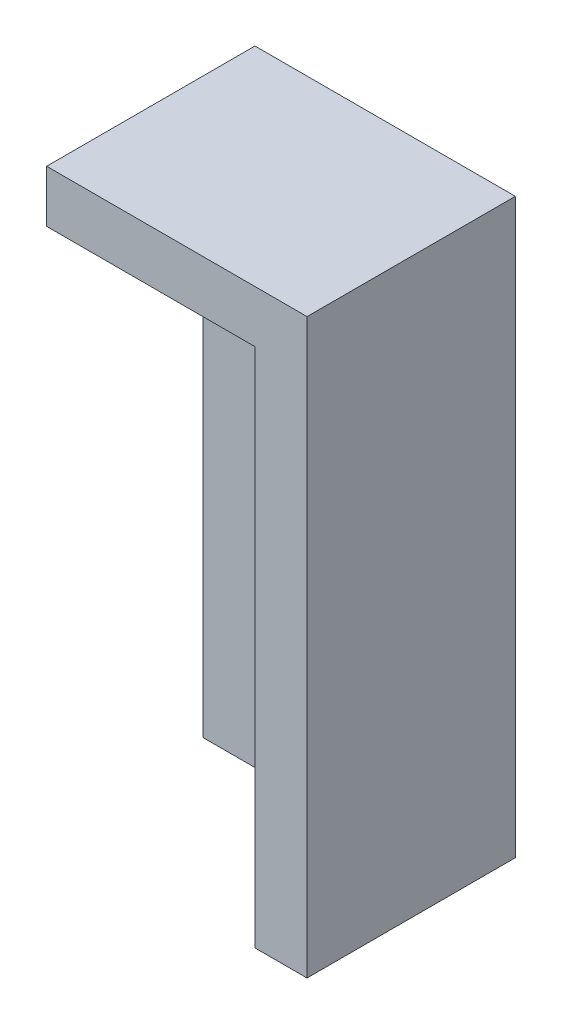
SolidWorks part; units mm, degrees
ref_plane "Front Plane" through (0, 0, 0) normal (1, 0, 0) x (0, 1, 0)
ref_plane "Top Plane" through (0, 0, 0) normal (0, 0, 1) x (0, 1, 0)
ref_plane "Right Plane" through (0, 0, 0) normal (0, 1, 0) x (-1, 0, 0)
sketch "Sketch1" plane through (0, 0, 0) normal (0, 0, 1) x (0, 1, 0)
  line L1 (-35.867, 2.791) -> (19.133, 2.791)
  line L2 (-35.867, 2.791) -> (-35.867, -22.209)
  line L3 (-35.867, -22.209) -> (19.133, -22.209)
  line L4 (19.133, 2.791) -> (19.133, -22.209)
  dimension "D1" = 55
  dimension "D2" = 25
extrude "Boss-Extrude1" add sketch "Sketch1" along normal blind 5
sketch "Sketch2" plane through (0, 0, 5) normal (0, 0, 1) x (1, 0, 0)
  line L0 (22.209, -35.867) -> (22.209, 19.133) construction
  line L1 (-2.791, 19.133) -> (22.209, 19.133)
  line L2 (-2.791, 19.133) -> (-2.791, 14.133)
  line L3 (-2.791, 14.133) -> (17.209, 14.133)
  line L4 (22.209, 19.133) -> (22.209, 4.133)
  line L5 (-2.791, -35.867) -> (22.209, -35.867) construction
  line L6 (22.209, 19.133) -> (17.209, 19.133)
  line L7 (22.209, 19.133) -> (22.209, -35.867)
  line L8 (22.209, -35.867) -> (17.209, -35.867)
  line L9 (17.209, 14.133) -> (17.209, -35.867)
  dimension "D1" = 5
  dimension "D2" = 5
sketch "Sketch3" plane through (0, 0, 5) normal (0, 0, 1) x (1, 0, 0)
  line L0 (-2.791, 14.133) -> (-2.791, 19.133)
  line L1 (-2.791, 19.133) -> (22.209, 19.133)
  line L2 (22.209, 19.133) -> (22.209, -35.867)
  line L3 (22.209, -35.867) -> (17.209, -35.867)
  line L4 (17.209, -35.867) -> (17.209, 14.133)
  line L5 (17.209, 14.133) -> (-2.791, 14.133)
extrude "Boss-Extrude2" add sketch "Sketch3" along normal blind 15
